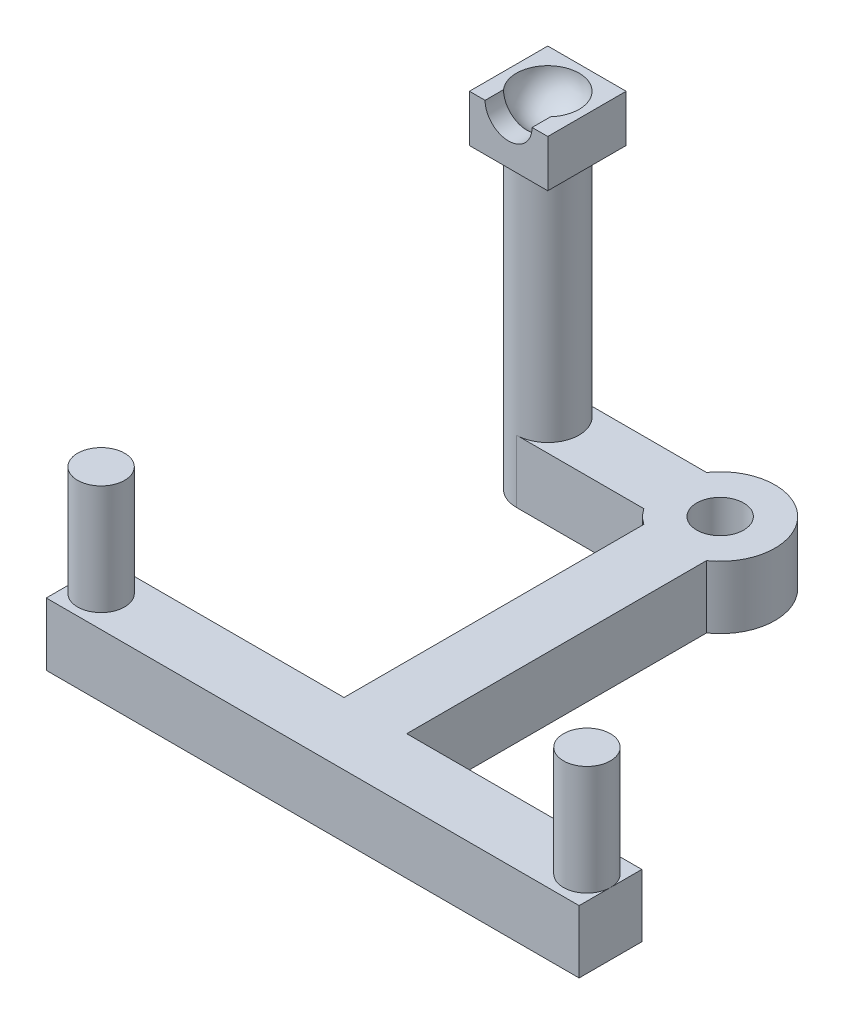
SolidWorks part; units mm, degrees
ref_plane "Front Plane" through (0, 0, 0) normal (0, 0, 1) x (1, 0, 0)
ref_plane "Top Plane" through (0, 0, 0) normal (0, 1, 0) x (1, 0, 0)
ref_plane "Right Plane" through (0, 0, 0) normal (1, 0, 0) x (0, 0, -1)
sketch "Sketch1" plane through (0, 0, 0) normal (0, 1, 0) x (1, 0, 0)
  line L0 (66.2501, -31.7392) -> (174.9726, -31.7392) construction
  line L1 (85, 124.0652) -> (85, -35.793) construction
  line L2 (0, 0) -> (170, 0)
  line L3 (0, 0) -> (0, 20)
  line L4 (0, 20) -> (170, 20)
  line L5 (170, 0) -> (170, 20)
  line L6 (75, 120) -> (95, 120)
  line L7 (75, 120) -> (75, 20)
  line L8 (75, 20) -> (95, 20)
  line L9 (95, 120) -> (95, 20)
  circle A0 centre (162.5, 10) radius 7.5
  circle A1 centre (7.5, 10) radius 7.5
  circle A2 centre (85, 130) radius 7.5
  circle A3 centre (85, 130) radius 17.5
  point P21 (0, 10)
  dimension "D4" = 15
  dimension "D7" = 15
  dimension "D1" = 100
  dimension "D10" = 15
  dimension "D11" = 35
  dimension "D2" = 75
  dimension "D3" = 20
  dimension "D5" = 10
  dimension "D6" = 10
  dimension "D8" = 20
  dimension "D9" = 75
  dimension "D12" = 10
  dimension "D13" = 85
extrude "Boss-Extrude9" add sketch "Sketch1" against normal blind 20 contours A3 L7 L4 L9 | L7 A3 L9 L6 | L9 A3 L7 L6 A2
sketch "Sketch3" plane through (0, 0, 0) normal (0, 1, 0) x (1, 0, 0)
  line L0 (0, 20) -> (75, 20) construction
  line L1 (95, 20) -> (170, 20) construction
  line L2 (0, 0) -> (0, 20) construction
  line L3 (170, 0) -> (170, 20) construction
  circle A0 centre (7.5, 10) radius 7.5
  circle A1 centre (162.5, 10) radius 7.5
  dimension "D1" = 15
  dimension "D2" = 15
  dimension "D4" = 10
  dimension "D3" = 10
extrude "Boss-Extrude10" add sketch "Sketch3" along normal blind 35
ref_plane "Plane5" through (75, 0, 0) normal (-1, 0, 0) x (0, 0, 1)
sketch "Sketch5" plane through (75, 0, 0) normal (-1, 0, 0) x (0, 0, 1)
  line L0 (-115.6386, 0) -> (-147.5, 0) construction
  line L1 (-140, 0) -> (-120, 0)
  line L2 (-140, 0) -> (-140, -20)
  line L3 (-140, -20) -> (-120, -20)
  line L4 (-120, 0) -> (-120, -20)
  line L5 (-147.5, -20) -> (-115.6386, -20) construction
  line L6 (120.6519, 245.4976) -> (425.3186, 245.4976) construction
  line L7 (-20, -20) -> (-20, 0) construction
  dimension "D1" = 100
  dimension "D2" = 20
extrude "Boss-Extrude11" add sketch "Sketch5" along normal blind 55
sketch "Sketch6" plane through (0, 0, 0) normal (0, 1, 0) x (1, 0, 0)
  line L0 (20, 140) -> (70.6386, 140) construction
  line L3 (20, 120) -> (20, 140)
  circle A1 centre (30, 130) radius 10
  dimension "D1" = 20
extrude "Cut-Extrude2" cut sketch "Sketch6" against normal through all
sketch "Sketch10" plane through (0, 0, 0) normal (0, 1, 0) x (1, 0, 0)
  circle A0 centre (30, 130) radius 10
  arc A1 (30, 140) -> (30, 120) centre (30, 130) ccw construction
  dimension "D1" = 20
extrude "Boss-Extrude13" add sketch "Sketch10" along normal blind 75
sketch "Sketch12" plane through (0, 75, 0) normal (0, 1, 0) x (1, 0, 0)
  line L0 (20, 130) -> (40, 130) construction
  line L2 (17.5, 142.5) -> (42.5, 142.5)
  line L3 (17.5, 142.5) -> (17.5, 117.5)
  line L4 (17.5, 117.5) -> (42.5, 117.5)
  line L5 (42.5, 142.5) -> (42.5, 117.5)
  line L6 (17.5, 142.5) -> (42.5, 117.5) construction
  line L7 (17.5, 117.5) -> (42.5, 142.5) construction
  circle A0 centre (30, 130) radius 10 construction
  point P6 (30, 130)
  dimension "D1" = 25
  dimension "D2" = 25
extrude "Boss-Extrude14" add sketch "Sketch12" along normal blind 15
sketch "Sketch20" plane through (0, 90, 0) normal (0, 1, 0) x (1, 0, 0)
  line L0 (30, 142.5) -> (30, 117.5) construction
  line L1 (42.5, 142.5) -> (17.5, 142.5) construction
  line L2 (17.5, 117.5) -> (42.5, 117.5) construction
  line L3 (30, 140) -> (30, 120)
  arc A0 (30, 120) -> (30, 140) centre (30, 130) ccw
  dimension "D1" = 10
revolve "Cut-Revolve5" cut sketch "Sketch20" angle 360 about L3
sketch "Sketch21" plane through (0, 0, -117.5) normal (0, 0, 1) x (1, 0, 0)
  line L0 (17.5, 90) -> (42.5, 90) construction
  circle A0 centre (30, 90) radius 7.5
  dimension "D1" = 15
extrude "Cut-Extrude8" cut sketch "Sketch21" against normal blind 8 contours A0
